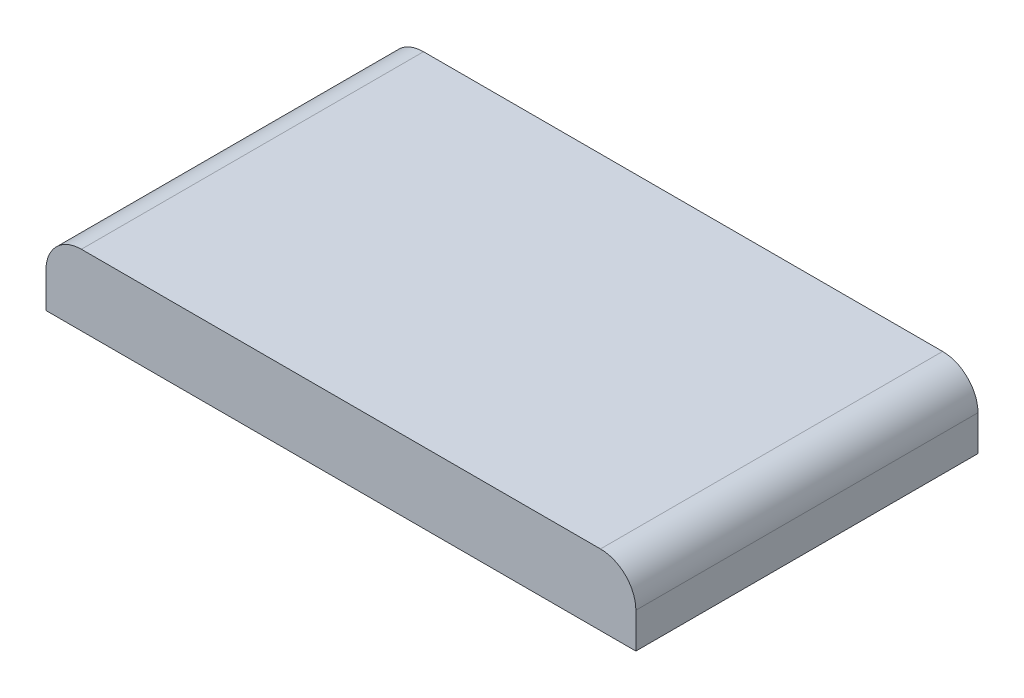
SolidWorks part; units mm, degrees
ref_plane "Front Plane" through (0, 0, 0) normal (0, 0, 1) x (1, 0, 0)
ref_plane "Top Plane" through (0, 0, 0) normal (0, 1, 0) x (1, 0, 0)
ref_plane "Right Plane" through (0, 0, 0) normal (1, 0, 0) x (0, 0, -1)
sketch "Sketch1" plane through (0, 0, 0) normal (0, 1, 0) x (1, 0, 0)
  line L1 (-121.3881, 83.5949) -> (5.6119, 83.5949)
  line L2 (-121.3881, 83.5949) -> (-121.3881, 9.9349)
  line L3 (-121.3881, 9.9349) -> (5.6119, 9.9349)
  line L4 (5.6119, 83.5949) -> (5.6119, 9.9349)
  dimension "D1" = 127
  dimension "D2" = 73.66
  dimension "D3" = 5.6119
  dimension "D4" = 9.9349
extrude "Boss-Extrude1" add sketch "Sketch1" along normal blind 15.24
fillet "Fillet1" radius 7.62 2 edges at (-121.3881, 15.24, -46.7649) (5.6119, 15.24, -46.7649)
